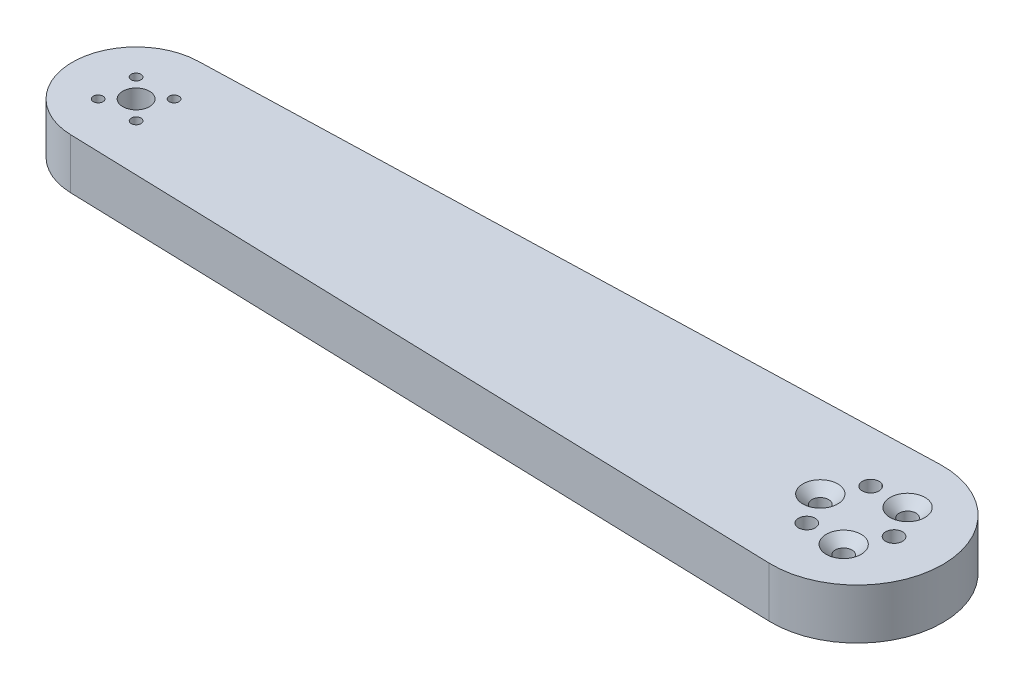
SolidWorks part; units mm, degrees
ref_plane "前视基准面" through (0, 0, 0) normal (0, 0, 1) x (1, 0, 0)
ref_plane "上视基准面" through (0, 0, 0) normal (0, 1, 0) x (1, 0, 0)
ref_plane "右视基准面" through (0, 0, 0) normal (1, 0, 0) x (0, 0, -1)
sketch "草图1" plane through (0, 0, 0) normal (0, 1, 0) x (1, 0, 0)
  line L0 (0, 0) -> (136.444, 0) construction
  line L1 (-0.5744, 18.9913) -> (214.2291, 25.4883)
  line L2 (-0.5744, -18.9913) -> (214.2291, -25.4883)
  line L4 (220.5, -9.5263) -> (226, 0) construction
  line L5 (226, 0) -> (220.5, 9.5263) construction
  line L6 (220.5, 9.5263) -> (209.5, 9.5263) construction
  line L7 (209.5, 9.5263) -> (204, 0) construction
  line L8 (204, 0) -> (209.5, -9.5263) construction
  line L9 (209.5, -9.5263) -> (220.5, -9.5263) construction
  line L10 (-5.6569, -5.6569) -> (5.6569, -5.6569) construction
  line L11 (5.6569, -5.6569) -> (5.6569, 5.6569) construction
  line L12 (5.6569, 5.6569) -> (-5.6569, 5.6569) construction
  line L13 (-5.6569, 5.6569) -> (-5.6569, -5.6569) construction
  circle A0 centre (0, 0) radius 4
  circle A1 centre (0, 0) radius 19 construction
  circle A3 centre (215, 0) radius 25.5 construction
  arc A4 (214.2291, 25.4883) -> (214.2291, -25.4883) centre (215, 0) cw
  arc A5 (-0.5744, 18.9913) -> (-0.5744, -18.9913) centre (0, 0) ccw
  circle A6 centre (215, 0) radius 11 construction
  circle A7 centre (215, 0) radius 9.5263 construction
  circle A8 centre (209.5, 9.5263) radius 2.5
  circle A9 centre (220.5, 9.5263) radius 2.5
  circle A10 centre (226, 0) radius 2.5
  circle A11 centre (220.5, -9.5263) radius 2.5
  circle A12 centre (209.5, -9.5263) radius 2.5
  circle A13 centre (204, 0) radius 2.5
  circle A14 centre (0, 0) radius 8 construction
  circle A15 centre (0, 0) radius 5.6569 construction
  circle A16 centre (-5.6569, 5.6569) radius 1.45
  circle A17 centre (5.6569, 5.6569) radius 1.45
  circle A18 centre (5.6569, -5.6569) radius 1.45
  circle A19 centre (-5.6569, -5.6569) radius 1.45
  dimension "D1" = 8
  dimension "D2" = 38
  dimension "D3" = 22
  dimension "D5" = 51
  dimension "D6" = 5
  dimension "D7" = 16
  dimension "D8" = 2.9
  dimension "D4" = 215
extrude "凸台-拉伸1" add sketch "草图1" along normal blind 15
chamfer "倒角1" distance 1.8 angle 45 4 edges at (-5.6569, 0, 7.1069) (5.6569, 0, 7.1069) (-5.6569, 0, -4.2069) (5.6569, 0, -4.2069)
chamfer "倒角2" distance 2.7 angle 45 3 edges at (220.5, 15, -7.0263) (204, 15, 2.5) (220.5, 15, 12.0263)
